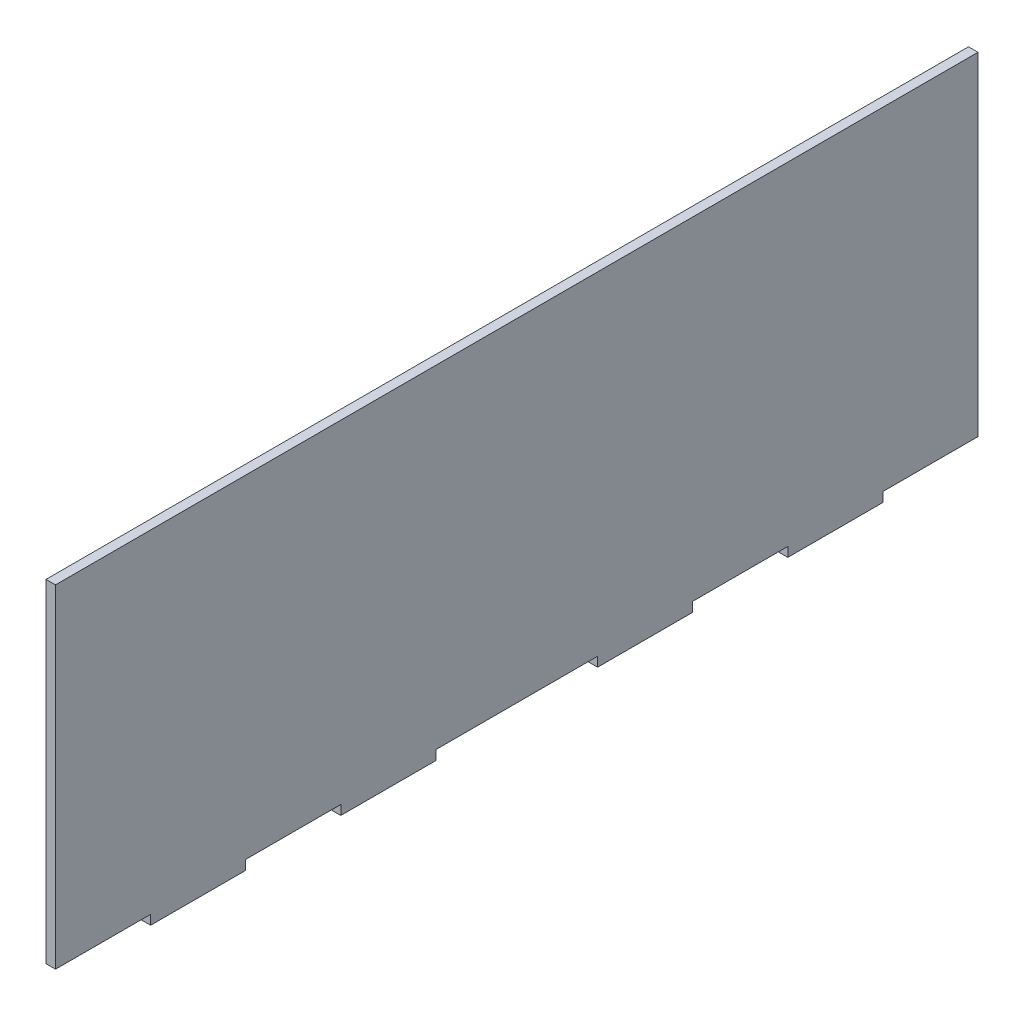
SolidWorks part; units mm, degrees
ref_plane "Front Plane" through (0, 0, 0) normal (0, 0, 1) x (1, 0, 0)
ref_plane "Top Plane" through (0, 0, 0) normal (0, 1, 0) x (1, 0, 0)
ref_plane "Right Plane" through (0, 0, 0) normal (1, 0, 0) x (0, 0, -1)
sketch "Sketch1" plane through (0, 0, 0) normal (1, 0, 0) x (0, 0, -1)
  line L0 (0, 55) -> (0, -55) construction
  line L1 (-97, -35) -> (97, -35)
  line L2 (-97, -35) -> (-97, 0)
  line L3 (-97, 35) -> (97, 35)
  line L4 (97, -35) -> (97, 0)
  line L5 (-97, -35) -> (97, 35) construction
  line L6 (-97, 35) -> (97, -35) construction
  line L7 (-97, 20) -> (-99, 20)
  line L9 (-97, 0) -> (-99, 0)
  line L10 (-99, 20) -> (-99, 0)
  line L11 (97, 0) -> (99, 0)
  line L12 (99, 20) -> (99, 0)
  line L13 (97, 20) -> (99, 20)
  line L15 (-97, 20) -> (-97, 35)
  line L16 (97, 20) -> (97, 35)
  point P0 (0, 0)
  point P10 (-98, 20)
  dimension "D1" = 194
  dimension "D2" = 70
  dimension "D3" = 20
  dimension "D4" = 2
  dimension "D5" = 15
extrude "Boss-Extrude1" add sketch "Sketch1" along normal blind 2
sketch "Sketch2" plane through (2, 0, 0) normal (1, 0, 0) x (0, 0, -1)
  line L1 (-99, 20) -> (-97, 20)
  line L2 (-99, 20) -> (-99, 0)
  line L3 (-99, 0) -> (-97, 0)
  line L4 (-97, 20) -> (-97, 0)
  line L5 (97, 20) -> (99, 20)
  line L6 (97, 20) -> (97, 0)
  line L7 (97, 0) -> (99, 0)
  line L8 (99, 20) -> (99, 0)
extrude "Cut-Extrude1" cut sketch "Sketch2" against normal blind 10
sketch "Sketch3" plane through (2, 0, 0) normal (1, 0, 0) x (0, 0, -1)
  line L0 (-97, -35) -> (97, -35) construction
  line L1 (-77, -35) -> (-57, -35)
  line L2 (-77, -35) -> (-77, -37)
  line L3 (-77, -37) -> (-57, -37)
  line L4 (-57, -35) -> (-57, -37)
  line L5 (-97, 35) -> (-97, -35) construction
  line L6 (-37, -35) -> (-17, -35)
  line L7 (-37, -35) -> (-37, -37)
  line L8 (-37, -37) -> (-17, -37)
  line L9 (-17, -35) -> (-17, -37)
  line L10 (0, 55) -> (0, -55) construction
  line L11 (37, -37) -> (17, -37)
  line L12 (17, -35) -> (17, -37)
  line L13 (37, -35) -> (17, -35)
  line L14 (37, -35) -> (37, -37)
  line L15 (77, -37) -> (57, -37)
  line L16 (57, -35) -> (57, -37)
  line L17 (77, -35) -> (57, -35)
  line L18 (77, -35) -> (77, -37)
  dimension "D1" = 20
  dimension "D2" = 2
  dimension "D3" = 2
  dimension "D4" = 20
  dimension "D5" = 20
  dimension "D6" = 20
extrude "Boss-Extrude2" add sketch "Sketch3" against normal blind 2
